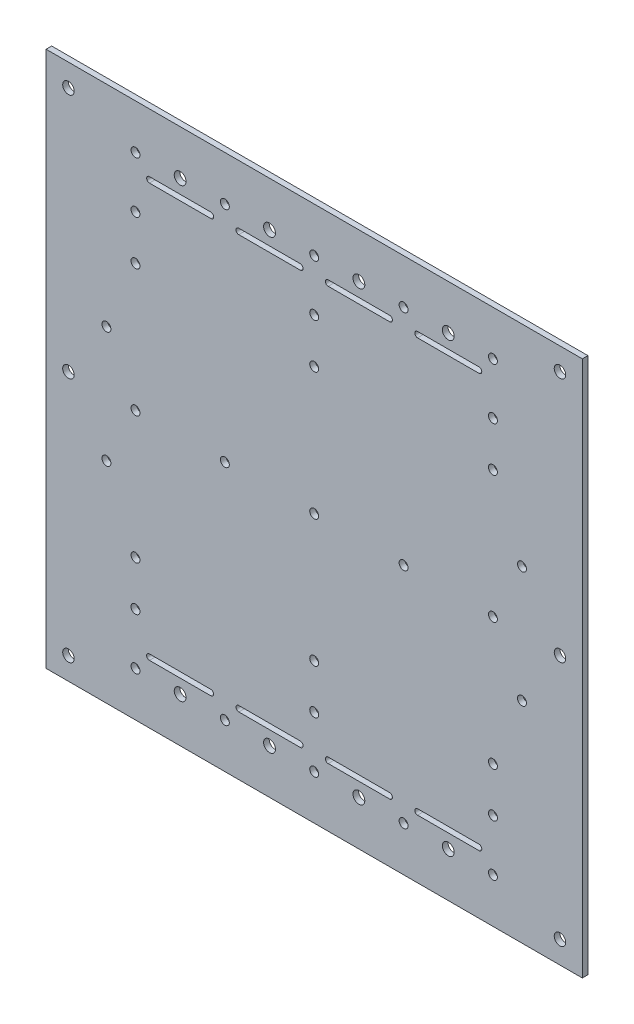
SolidWorks part; units mm, degrees
ref_plane "Front Plane" through (0, 0, 0) normal (0, 0, 1) x (1, 0, 0)
ref_plane "Top Plane" through (0, 0, 0) normal (0, 1, 0) x (1, 0, 0)
ref_plane "Right Plane" through (0, 0, 0) normal (1, 0, 0) x (0, 0, -1)
sketch "Sketch1" plane through (0, 0, 0) normal (0, 0, 1) x (1, 0, 0)
  line L0 (-152.4, 127) -> (-76.2, 127) construction
  line L1 (-152.4, 152.4) -> (152.4, 152.4)
  line L2 (-152.4, 152.4) -> (-152.4, -152.4)
  line L3 (-152.4, -152.4) -> (152.4, -152.4)
  line L4 (152.4, 152.4) -> (152.4, -152.4)
  line L5 (-76.2, 127) -> (-25.4, 127) construction
  line L6 (-25.4, 127) -> (25.4, 127) construction
  line L7 (25.4, 127) -> (76.2, 127) construction
  line L8 (76.2, 127) -> (152.4, 127) construction
  line L9 (-152.4, 0) -> (152.4, 0) construction
  line L10 (0, 152.4) -> (0, -152.4) construction
  line L11 (-118.11, 152.4) -> (-118.11, -152.4) construction
  line L12 (-152.4, -127) -> (152.4, -127) construction
  line L13 (127, 152.4) -> (127, -152.4) construction
  line L14 (-50.8, 152.4) -> (-50.8, -152.4) construction
  line L15 (50.8, 152.4) -> (50.8, -152.4) construction
  line L16 (-101.6, 152.4) -> (-101.6, -152.4) construction
  line L17 (-95.25, 66.04) -> (-57.15, 66.04) construction
  line L18 (-95.25, 66.04) -> (-95.25, -66.04) construction
  line L19 (-95.25, -66.04) -> (-57.15, -66.04) construction
  line L20 (-57.15, 66.04) -> (-57.15, -66.04) construction
  line L21 (-44.45, 66.04) -> (-6.35, 66.04) construction
  line L22 (-44.45, 66.04) -> (-44.45, -66.04) construction
  line L23 (-44.45, -66.04) -> (-6.35, -66.04) construction
  line L24 (-6.35, 66.04) -> (-6.35, -66.04) construction
  line L25 (6.35, 66.04) -> (44.45, 66.04) construction
  line L26 (6.35, 66.04) -> (6.35, -66.04) construction
  line L27 (6.35, -66.04) -> (44.45, -66.04) construction
  line L28 (44.45, 66.04) -> (44.45, -66.04) construction
  line L29 (57.15, 66.04) -> (95.25, 66.04) construction
  line L30 (57.15, 66.04) -> (57.15, -66.04) construction
  line L31 (57.15, -66.04) -> (95.25, -66.04) construction
  line L32 (95.25, 66.04) -> (95.25, -66.04) construction
  line L33 (101.6, 152.4) -> (101.6, -152.4) construction
  line L34 (-152.4, 120.65) -> (152.4, 120.65) construction
  line L35 (-101.6, 39.7057) -> (-95.25, 39.7057) construction
  line L36 (-57.15, 39.7057) -> (-50.8, 39.7057) construction
  line L37 (-76.2, 66.04) -> (-76.2, 0) construction
  line L38 (-76.2, 0) -> (-76.2, -66.04) construction
  line L39 (-152.4, 72.39) -> (152.4, 72.39) construction
  line L40 (-152.4, -72.39) -> (152.4, -72.39) construction
  line L41 (-76.2, 66.04) -> (-76.2, 72.39) construction
  line L42 (-95.25, -66.04) -> (-95.25, -72.39) construction
  line L43 (95.25, 39.7057) -> (101.6, 39.7057) construction
  line L44 (-95.25, 111.76) -> (-57.15, 111.76) construction
  line L45 (-57.15, 111.76) -> (-57.15, 118.4779) construction
  line L46 (-94.0266, 120.65) -> (-78.1749, 130.2582) construction
  line L47 (-95.25, 111.76) -> (-95.25, 118.4779) construction
  line L48 (-58.3734, 120.65) -> (-74.2251, 130.2582) construction
  line L49 (-107.3169, 130.81) -> (-83.1894, 130.81) construction
  line L50 (-6.35, 111.76) -> (-6.35, 118.4779) construction
  line L51 (-7.5734, 120.65) -> (-23.4251, 130.2582) construction
  line L52 (-43.2266, 120.65) -> (-27.3749, 130.2582) construction
  line L53 (-44.45, 111.76) -> (-44.45, 118.4779) construction
  line L54 (-6.35, 111.76) -> (-44.45, 111.76) construction
  line L55 (44.45, 111.76) -> (44.45, 118.4779) construction
  line L56 (43.2266, 120.65) -> (27.3749, 130.2582) construction
  line L57 (7.5734, 120.65) -> (23.4251, 130.2582) construction
  line L58 (6.35, 111.76) -> (6.35, 118.4779) construction
  line L59 (6.35, 111.76) -> (44.45, 111.76) construction
  line L60 (95.25, 111.76) -> (57.15, 111.76) construction
  line L61 (95.25, 111.76) -> (95.25, 118.4779) construction
  line L62 (94.0266, 120.65) -> (78.1749, 130.2582) construction
  line L63 (58.3734, 120.65) -> (74.2251, 130.2582) construction
  line L64 (57.15, 111.76) -> (57.15, 118.4779) construction
  line L65 (-95.25, -111.76) -> (-95.25, -118.4779) construction
  line L66 (-94.0266, -120.65) -> (-78.1749, -130.2582) construction
  line L67 (-58.3734, -120.65) -> (-74.2251, -130.2582) construction
  line L68 (-95.25, -111.76) -> (-57.15, -111.76) construction
  line L69 (-57.15, -111.76) -> (-57.15, -118.4779) construction
  line L70 (-44.45, -111.76) -> (-44.45, -118.4779) construction
  line L71 (-43.2266, -120.65) -> (-27.3749, -130.2582) construction
  line L72 (-6.35, -111.76) -> (-44.45, -111.76) construction
  line L73 (-7.5734, -120.65) -> (-23.4251, -130.2582) construction
  line L74 (-6.35, -111.76) -> (-6.35, -118.4779) construction
  line L75 (6.35, -111.76) -> (6.35, -118.4779) construction
  line L76 (7.5734, -120.65) -> (23.4251, -130.2582) construction
  line L77 (43.2266, -120.65) -> (27.3749, -130.2582) construction
  line L78 (6.35, -111.76) -> (44.45, -111.76) construction
  line L79 (44.45, -111.76) -> (44.45, -118.4779) construction
  line L80 (57.15, -111.76) -> (57.15, -118.4779) construction
  line L81 (58.3734, -120.65) -> (74.2251, -130.2582) construction
  line L82 (94.0266, -120.65) -> (78.1749, -130.2582) construction
  line L83 (95.25, -111.76) -> (57.15, -111.76) construction
  line L84 (95.25, -111.76) -> (95.25, -118.4779) construction
  line L85 (-152.4, 97.79) -> (152.4, 97.79) construction
  line L86 (-50.8, 39.7057) -> (-44.45, 39.7057) construction
  line L87 (-127, 152.4) -> (-127, -152.4) construction
  line L89 (-95.25, 101.6) -> (-92.3192, 101.6) construction
  line L90 (-95.25, 101.6) -> (-95.25, -101.6) construction
  line L96 (-90.8538, 101.6) -> (-90.8538, 68.58) construction
  line L97 (-89.3885, 101.6) -> (-89.3885, 68.58) construction
  line L98 (-92.3192, 101.6) -> (-92.3192, 68.58) construction
  line L99 (-83.5269, 101.6) -> (-83.5269, 68.58) construction
  line L100 (-86.4577, 101.6) -> (-86.4577, 68.58) construction
  line L101 (-89.3885, 101.6) -> (-86.4577, 101.6) construction
  line L102 (-77.6654, 101.6) -> (-77.6654, 68.58) construction
  line L103 (-80.5962, 101.6) -> (-80.5962, 68.58) construction
  line L104 (-83.5269, 101.6) -> (-80.5962, 101.6) construction
  line L105 (-71.8038, 101.6) -> (-71.8038, 68.58) construction
  line L106 (-74.7346, 101.6) -> (-74.7346, 68.58) construction
  line L107 (-77.6654, 101.6) -> (-74.7346, 101.6) construction
  line L108 (-65.9423, 101.6) -> (-65.9423, 68.58) construction
  line L109 (-68.8731, 101.6) -> (-68.8731, 68.58) construction
  line L110 (-71.8038, 101.6) -> (-68.8731, 101.6) construction
  line L111 (-60.0808, 101.6) -> (-60.0808, 68.58) construction
  line L112 (-63.0115, 101.6) -> (-63.0115, 68.58) construction
  line L113 (-65.9423, 101.6) -> (-63.0115, 101.6) construction
  line L114 (-57.15, -101.6) -> (-57.15, 101.6) construction
  line L115 (-60.0808, 101.6) -> (-57.15, 101.6) construction
  line L116 (-92.3192, 68.58) -> (-89.3885, 68.58) construction
  line L117 (-60.0808, -101.6) -> (-57.15, -101.6) construction
  line L118 (-60.0808, -101.6) -> (-60.0808, -68.58) construction
  line L119 (-63.0115, -101.6) -> (-63.0115, -68.58) construction
  line L120 (-65.9423, -101.6) -> (-65.9423, -68.58) construction
  line L121 (-65.9423, -101.6) -> (-63.0115, -101.6) construction
  line L122 (-68.8731, -101.6) -> (-68.8731, -68.58) construction
  line L123 (-71.8038, -101.6) -> (-68.8731, -101.6) construction
  line L124 (-71.8038, -101.6) -> (-71.8038, -68.58) construction
  line L125 (-74.7346, -101.6) -> (-74.7346, -68.58) construction
  line L126 (-77.6654, -101.6) -> (-74.7346, -101.6) construction
  line L127 (-77.6654, -101.6) -> (-77.6654, -68.58) construction
  line L128 (-80.5962, -101.6) -> (-80.5962, -68.58) construction
  line L129 (-83.5269, -101.6) -> (-80.5962, -101.6) construction
  line L130 (-83.5269, -101.6) -> (-83.5269, -68.58) construction
  line L131 (-86.4577, -101.6) -> (-86.4577, -68.58) construction
  line L132 (-89.3885, -101.6) -> (-86.4577, -101.6) construction
  line L133 (-89.3885, -101.6) -> (-89.3885, -68.58) construction
  line L134 (-92.3192, -101.6) -> (-92.3192, -68.58) construction
  line L135 (-95.25, -101.6) -> (-92.3192, -101.6) construction
  line L136 (-9.2808, 68.58) -> (-12.2115, 68.58) construction
  line L137 (6.35, 66.04) -> (44.45, 66.04) construction
  line L138 (-6.35, -66.04) -> (-6.35, -72.39) construction
  line L139 (-25.4, 66.04) -> (-25.4, 72.39) construction
  line L140 (-25.4, 0) -> (-25.4, -66.04) construction
  line L141 (-25.4, 66.04) -> (-25.4, 0) construction
  line L142 (-44.45, 66.04) -> (-44.45, -66.04) construction
  line L143 (-6.35, -66.04) -> (-44.45, -66.04) construction
  line L144 (-6.35, 66.04) -> (-6.35, -66.04) construction
  line L145 (-6.35, 66.04) -> (-44.45, 66.04) construction
  line L146 (-6.35, -101.6) -> (-9.2808, -101.6) construction
  line L147 (-9.2808, -101.6) -> (-9.2808, -68.58) construction
  line L148 (-12.2115, -101.6) -> (-12.2115, -68.58) construction
  line L149 (-12.2115, -101.6) -> (-15.1423, -101.6) construction
  line L150 (-15.1423, -101.6) -> (-15.1423, -68.58) construction
  line L151 (-18.0731, -101.6) -> (-18.0731, -68.58) construction
  line L152 (-18.0731, -101.6) -> (-21.0038, -101.6) construction
  line L153 (-21.0038, -101.6) -> (-21.0038, -68.58) construction
  line L154 (-23.9346, -101.6) -> (-23.9346, -68.58) construction
  line L155 (-23.9346, -101.6) -> (-26.8654, -101.6) construction
  line L156 (-26.8654, -101.6) -> (-26.8654, -68.58) construction
  line L157 (-29.7962, -101.6) -> (-29.7962, -68.58) construction
  line L158 (-29.7962, -101.6) -> (-32.7269, -101.6) construction
  line L159 (-32.7269, -101.6) -> (-32.7269, -68.58) construction
  line L160 (-35.6577, -101.6) -> (-38.5885, -101.6) construction
  line L161 (-35.6577, -101.6) -> (-35.6577, -68.58) construction
  line L162 (-38.5885, -101.6) -> (-38.5885, -68.58) construction
  line L163 (-41.5192, -101.6) -> (-41.5192, -68.58) construction
  line L164 (-41.5192, -101.6) -> (-44.45, -101.6) construction
  line L165 (-41.5192, 101.6) -> (-44.45, 101.6) construction
  line L166 (-44.45, -101.6) -> (-44.45, 101.6) construction
  line L167 (-35.6577, 101.6) -> (-38.5885, 101.6) construction
  line L168 (-38.5885, 101.6) -> (-38.5885, 68.58) construction
  line L169 (-41.5192, 101.6) -> (-41.5192, 68.58) construction
  line L170 (-29.7962, 101.6) -> (-32.7269, 101.6) construction
  line L171 (-32.7269, 101.6) -> (-32.7269, 68.58) construction
  line L172 (-35.6577, 101.6) -> (-35.6577, 68.58) construction
  line L173 (-23.9346, 101.6) -> (-26.8654, 101.6) construction
  line L174 (-26.8654, 101.6) -> (-26.8654, 68.58) construction
  line L175 (-29.7962, 101.6) -> (-29.7962, 68.58) construction
  line L176 (-18.0731, 101.6) -> (-21.0038, 101.6) construction
  line L177 (-21.0038, 101.6) -> (-21.0038, 68.58) construction
  line L178 (-23.9346, 101.6) -> (-23.9346, 68.58) construction
  line L179 (-12.2115, 101.6) -> (-15.1423, 101.6) construction
  line L180 (-15.1423, 101.6) -> (-15.1423, 68.58) construction
  line L181 (-18.0731, 101.6) -> (-18.0731, 68.58) construction
  line L182 (-9.2808, 101.6) -> (-9.2808, 68.58) construction
  line L183 (-12.2115, 101.6) -> (-12.2115, 68.58) construction
  line L184 (-6.35, 101.6) -> (-6.35, -101.6) construction
  line L185 (-6.35, 101.6) -> (-9.2808, 101.6) construction
  line L186 (6.35, 66.04) -> (6.35, -66.04) construction
  line L187 (6.35, -66.04) -> (44.45, -66.04) construction
  line L188 (44.45, 66.04) -> (44.45, -66.04) construction
  line L189 (25.4, 66.04) -> (25.4, 0) construction
  line L190 (25.4, 0) -> (25.4, -66.04) construction
  line L191 (25.4, 66.04) -> (25.4, 72.39) construction
  line L192 (6.35, -66.04) -> (6.35, -72.39) construction
  line L193 (9.2808, 68.58) -> (12.2115, 68.58) construction
  line L194 (6.35, 66.04) -> (6.35, -66.04) construction
  line L195 (44.45, -66.04) -> (6.35, -66.04) construction
  line L196 (44.45, 66.04) -> (44.45, -66.04) construction
  line L197 (44.45, 66.04) -> (6.35, 66.04) construction
  line L198 (6.35, 101.6) -> (9.2808, 101.6) construction
  line L199 (6.35, 101.6) -> (6.35, -101.6) construction
  line L200 (12.2115, 101.6) -> (12.2115, 68.58) construction
  line L201 (9.2808, 101.6) -> (9.2808, 68.58) construction
  line L202 (18.0731, 101.6) -> (18.0731, 68.58) construction
  line L203 (15.1423, 101.6) -> (15.1423, 68.58) construction
  line L204 (12.2115, 101.6) -> (15.1423, 101.6) construction
  line L205 (23.9346, 101.6) -> (23.9346, 68.58) construction
  line L206 (21.0038, 101.6) -> (21.0038, 68.58) construction
  line L207 (18.0731, 101.6) -> (21.0038, 101.6) construction
  line L208 (29.7962, 101.6) -> (29.7962, 68.58) construction
  line L209 (26.8654, 101.6) -> (26.8654, 68.58) construction
  line L210 (23.9346, 101.6) -> (26.8654, 101.6) construction
  line L211 (35.6577, 101.6) -> (35.6577, 68.58) construction
  line L212 (32.7269, 101.6) -> (32.7269, 68.58) construction
  line L213 (29.7962, 101.6) -> (32.7269, 101.6) construction
  line L214 (41.5192, 101.6) -> (41.5192, 68.58) construction
  line L215 (38.5885, 101.6) -> (38.5885, 68.58) construction
  line L216 (35.6577, 101.6) -> (38.5885, 101.6) construction
  line L217 (44.45, -101.6) -> (44.45, 101.6) construction
  line L218 (41.5192, 101.6) -> (44.45, 101.6) construction
  line L219 (41.5192, -101.6) -> (44.45, -101.6) construction
  line L220 (41.5192, -101.6) -> (41.5192, -68.58) construction
  line L221 (38.5885, -101.6) -> (38.5885, -68.58) construction
  line L222 (35.6577, -101.6) -> (35.6577, -68.58) construction
  line L223 (35.6577, -101.6) -> (38.5885, -101.6) construction
  line L224 (32.7269, -101.6) -> (32.7269, -68.58) construction
  line L225 (29.7962, -101.6) -> (32.7269, -101.6) construction
  line L226 (29.7962, -101.6) -> (29.7962, -68.58) construction
  line L227 (26.8654, -101.6) -> (26.8654, -68.58) construction
  line L228 (23.9346, -101.6) -> (26.8654, -101.6) construction
  line L229 (23.9346, -101.6) -> (23.9346, -68.58) construction
  line L230 (21.0038, -101.6) -> (21.0038, -68.58) construction
  line L231 (18.0731, -101.6) -> (21.0038, -101.6) construction
  line L232 (18.0731, -101.6) -> (18.0731, -68.58) construction
  line L233 (15.1423, -101.6) -> (15.1423, -68.58) construction
  line L234 (12.2115, -101.6) -> (15.1423, -101.6) construction
  line L235 (12.2115, -101.6) -> (12.2115, -68.58) construction
  line L236 (9.2808, -101.6) -> (9.2808, -68.58) construction
  line L237 (6.35, -101.6) -> (9.2808, -101.6) construction
  line L238 (57.15, 66.04) -> (95.25, 66.04) construction
  line L239 (57.15, 66.04) -> (57.15, -66.04) construction
  line L240 (57.15, -66.04) -> (95.25, -66.04) construction
  line L241 (95.25, 66.04) -> (95.25, -66.04) construction
  line L242 (92.3192, 68.58) -> (89.3885, 68.58) construction
  line L243 (95.25, -66.04) -> (95.25, -72.39) construction
  line L244 (76.2, 66.04) -> (76.2, 72.39) construction
  line L245 (76.2, 0) -> (76.2, -66.04) construction
  line L246 (76.2, 66.04) -> (76.2, 0) construction
  line L247 (57.15, 66.04) -> (57.15, -66.04) construction
  line L248 (95.25, -66.04) -> (57.15, -66.04) construction
  line L249 (95.25, 66.04) -> (95.25, -66.04) construction
  line L250 (95.25, 66.04) -> (57.15, 66.04) construction
  line L251 (57.15, 66.04) -> (57.15, -66.04) construction
  line L252 (95.25, -66.04) -> (57.15, -66.04) construction
  line L253 (95.25, 66.04) -> (95.25, -66.04) construction
  line L254 (95.25, 66.04) -> (57.15, 66.04) construction
  line L255 (95.25, -101.6) -> (92.3192, -101.6) construction
  line L256 (92.3192, -101.6) -> (92.3192, -68.58) construction
  line L257 (89.3885, -101.6) -> (89.3885, -68.58) construction
  line L258 (89.3885, -101.6) -> (86.4577, -101.6) construction
  line L259 (86.4577, -101.6) -> (86.4577, -68.58) construction
  line L260 (83.5269, -101.6) -> (83.5269, -68.58) construction
  line L261 (83.5269, -101.6) -> (80.5962, -101.6) construction
  line L262 (80.5962, -101.6) -> (80.5962, -68.58) construction
  line L263 (77.6654, -101.6) -> (77.6654, -68.58) construction
  line L264 (77.6654, -101.6) -> (74.7346, -101.6) construction
  line L265 (74.7346, -101.6) -> (74.7346, -68.58) construction
  line L266 (71.8038, -101.6) -> (71.8038, -68.58) construction
  line L267 (71.8038, -101.6) -> (68.8731, -101.6) construction
  line L268 (68.8731, -101.6) -> (68.8731, -68.58) construction
  line L269 (65.9423, -101.6) -> (63.0115, -101.6) construction
  line L270 (65.9423, -101.6) -> (65.9423, -68.58) construction
  line L271 (63.0115, -101.6) -> (63.0115, -68.58) construction
  line L272 (60.0808, -101.6) -> (60.0808, -68.58) construction
  line L273 (60.0808, -101.6) -> (57.15, -101.6) construction
  line L274 (60.0808, 101.6) -> (57.15, 101.6) construction
  line L275 (57.15, -101.6) -> (57.15, 101.6) construction
  line L276 (65.9423, 101.6) -> (63.0115, 101.6) construction
  line L277 (63.0115, 101.6) -> (63.0115, 68.58) construction
  line L278 (60.0808, 101.6) -> (60.0808, 68.58) construction
  line L279 (71.8038, 101.6) -> (68.8731, 101.6) construction
  line L280 (68.8731, 101.6) -> (68.8731, 68.58) construction
  line L281 (65.9423, 101.6) -> (65.9423, 68.58) construction
  line L282 (77.6654, 101.6) -> (74.7346, 101.6) construction
  line L283 (74.7346, 101.6) -> (74.7346, 68.58) construction
  line L284 (71.8038, 101.6) -> (71.8038, 68.58) construction
  line L285 (83.5269, 101.6) -> (80.5962, 101.6) construction
  line L286 (80.5962, 101.6) -> (80.5962, 68.58) construction
  line L287 (77.6654, 101.6) -> (77.6654, 68.58) construction
  line L288 (89.3885, 101.6) -> (86.4577, 101.6) construction
  line L289 (86.4577, 101.6) -> (86.4577, 68.58) construction
  line L290 (83.5269, 101.6) -> (83.5269, 68.58) construction
  line L291 (92.3192, 101.6) -> (92.3192, 68.58) construction
  line L292 (89.3885, 101.6) -> (89.3885, 68.58) construction
  line L293 (95.25, 101.6) -> (95.25, -101.6) construction
  line L294 (95.25, 101.6) -> (92.3192, 101.6) construction
  line L295 (-101.6, 39.7057) -> (-107.95, 39.7057) construction
  line L296 (-101.6, 78.74) -> (101.6, 78.74) construction
  line L297 (-107.95, 72.39) -> (-107.95, -72.39) construction
  line L298 (-101.6, -78.74) -> (101.6, -78.74) construction
  line L299 (107.95, 72.39) -> (107.95, -72.39) construction
  line L300 (-97.0611, 78.74) -> (-97.0611, 72.39) construction
  line L301 (-107.95, 22.225) -> (-120.65, 22.225) construction
  line L302 (-127, 15.875) -> (-127, -15.875) construction
  line L303 (-120.65, -22.225) -> (-107.95, -22.225) construction
  line L304 (-93.6625, 117.475) -> (-58.7375, 117.475) construction
  line L305 (-93.6625, 119.0625) -> (-58.7375, 119.0625)
  line L306 (-93.6625, 115.8875) -> (-58.7375, 115.8875)
  line L307 (-7.9375, 117.475) -> (-42.8625, 117.475) construction
  line L308 (-7.9375, 119.0625) -> (-42.8625, 119.0625)
  line L309 (-7.9375, 115.8875) -> (-42.8625, 115.8875)
  line L310 (7.9375, 117.475) -> (42.8625, 117.475) construction
  line L311 (7.9375, 119.0625) -> (42.8625, 119.0625)
  line L312 (7.9375, 115.8875) -> (42.8625, 115.8875)
  line L313 (93.6625, 117.475) -> (58.7375, 117.475) construction
  line L314 (93.6625, 119.0625) -> (58.7375, 119.0625)
  line L315 (93.6625, 115.8875) -> (58.7375, 115.8875)
  line L316 (93.6625, -117.475) -> (58.7375, -117.475) construction
  line L317 (93.6625, -119.0625) -> (58.7375, -119.0625)
  line L318 (93.6625, -115.8875) -> (58.7375, -115.8875)
  line L319 (7.9375, -117.475) -> (42.8625, -117.475) construction
  line L320 (7.9375, -119.0625) -> (42.8625, -119.0625)
  line L321 (7.9375, -115.8875) -> (42.8625, -115.8875)
  line L322 (-7.9375, -117.475) -> (-42.8625, -117.475) construction
  line L323 (-7.9375, -119.0625) -> (-42.8625, -119.0625)
  line L324 (-7.9375, -115.8875) -> (-42.8625, -115.8875)
  line L325 (-93.6625, -117.475) -> (-58.7375, -117.475) construction
  line L326 (-93.6625, -119.0625) -> (-58.7375, -119.0625)
  line L327 (-93.6625, -115.8875) -> (-58.7375, -115.8875)
  line L328 (-6.35, 107.95) -> (-6.35, 95.25)
  line L329 (-95.25, 107.95) -> (-57.15, 107.95) construction
  line L330 (-95.25, 107.95) -> (-95.25, 95.25) construction
  line L331 (-95.25, 95.25) -> (-57.15, 95.25) construction
  line L332 (-57.15, 107.95) -> (-57.15, 95.25) construction
  line L333 (-6.35, 107.95) -> (-44.45, 107.95) construction
  line L334 (-44.45, 107.95) -> (-44.45, 95.25) construction
  line L335 (-6.35, 95.25) -> (-44.45, 95.25) construction
  line L336 (95.25, 95.25) -> (57.15, 95.25) construction
  line L337 (95.25, 107.95) -> (95.25, 95.25) construction
  line L338 (95.25, 107.95) -> (57.15, 107.95) construction
  line L339 (57.15, 107.95) -> (57.15, 95.25) construction
  line L340 (44.45, 107.95) -> (44.45, 95.25)
  line L341 (6.35, 95.25) -> (44.45, 95.25) construction
  line L342 (6.35, 107.95) -> (44.45, 107.95) construction
  line L343 (6.35, 107.95) -> (6.35, 95.25) construction
  line L344 (-95.25, -95.25) -> (-57.15, -95.25) construction
  line L345 (-95.25, -107.95) -> (-95.25, -95.25) construction
  line L346 (-95.25, -107.95) -> (-57.15, -107.95) construction
  line L347 (-57.15, -107.95) -> (-57.15, -95.25) construction
  line L348 (-44.45, -107.95) -> (-44.45, -95.25) construction
  line L349 (-6.35, -95.25) -> (-44.45, -95.25) construction
  line L350 (-6.35, -107.95) -> (-44.45, -107.95) construction
  line L351 (-6.35, -107.95) -> (-6.35, -95.25) construction
  line L352 (6.35, -107.95) -> (6.35, -95.25) construction
  line L353 (6.35, -95.25) -> (44.45, -95.25) construction
  line L354 (6.35, -107.95) -> (44.45, -107.95) construction
  line L355 (44.45, -107.95) -> (44.45, -95.25)
  line L356 (57.15, -107.95) -> (57.15, -95.25) construction
  line L357 (95.25, -107.95) -> (57.15, -107.95) construction
  line L358 (95.25, -107.95) -> (95.25, -95.25) construction
  line L359 (95.25, -95.25) -> (57.15, -95.25) construction
  circle A0 centre (-76.2, 127) radius 3.3655
  circle A1 centre (-25.4, 127) radius 3.3655
  circle A2 centre (25.4, 127) radius 3.3655
  circle A3 centre (76.2, 127) radius 3.3655
  circle A4 centre (-101.6, 0) radius 2.54
  circle A5 centre (-50.8, 0) radius 2.54
  circle A6 centre (0, 0) radius 2.54
  circle A7 centre (101.6, 0) radius 2.54
  circle A8 centre (50.8, 0) radius 2.54
  circle A9 centre (-50.8, 127) radius 2.54
  circle A10 centre (0, 127) radius 2.54
  circle A11 centre (50.8, 127) radius 2.54
  circle A12 centre (-101.6, 72.39) radius 2.54
  circle A13 centre (0, 72.39) radius 2.54
  circle A14 centre (101.6, 72.39) radius 2.54
  circle A15 centre (-101.6, -72.39) radius 2.54
  circle A16 centre (0, -72.39) radius 2.54
  circle A17 centre (101.6, -72.39) radius 2.54
  arc A18 (-74.2251, 130.2582) -> (-78.1749, 130.2582) centre (-76.2, 127) ccw construction
  arc A19 (-57.15, 118.4779) -> (-58.3734, 120.65) centre (-59.69, 118.4779) ccw construction
  arc A20 (-95.25, 118.4779) -> (-94.0266, 120.65) centre (-92.71, 118.4779) cw construction
  arc A21 (-6.35, 118.4779) -> (-7.5734, 120.65) centre (-8.89, 118.4779) ccw construction
  arc A22 (-27.3749, 130.2582) -> (-23.4251, 130.2582) centre (-25.4, 127) cw construction
  arc A23 (-44.45, 118.4779) -> (-43.2266, 120.65) centre (-41.91, 118.4779) cw construction
  arc A24 (44.45, 118.4779) -> (43.2266, 120.65) centre (41.91, 118.4779) ccw construction
  arc A25 (27.3749, 130.2582) -> (23.4251, 130.2582) centre (25.4, 127) ccw construction
  arc A26 (6.35, 118.4779) -> (7.5734, 120.65) centre (8.89, 118.4779) cw construction
  arc A27 (95.25, 118.4779) -> (94.0266, 120.65) centre (92.71, 118.4779) ccw construction
  arc A28 (74.2251, 130.2582) -> (78.1749, 130.2582) centre (76.2, 127) cw construction
  arc A29 (57.15, 118.4779) -> (58.3734, 120.65) centre (59.69, 118.4779) cw construction
  circle A30 centre (-76.2, -127) radius 3.3655
  circle A31 centre (-25.4, -127) radius 3.3655
  circle A32 centre (25.4, -127) radius 3.3655
  circle A33 centre (76.2, -127) radius 3.3655
  arc A34 (-95.25, -118.4779) -> (-94.0266, -120.65) centre (-92.71, -118.4779) ccw construction
  arc A35 (-74.2251, -130.2582) -> (-78.1749, -130.2582) centre (-76.2, -127) cw construction
  arc A36 (-57.15, -118.4779) -> (-58.3734, -120.65) centre (-59.69, -118.4779) cw construction
  arc A37 (-44.45, -118.4779) -> (-43.2266, -120.65) centre (-41.91, -118.4779) ccw construction
  arc A38 (-27.3749, -130.2582) -> (-23.4251, -130.2582) centre (-25.4, -127) ccw construction
  arc A39 (-6.35, -118.4779) -> (-7.5734, -120.65) centre (-8.89, -118.4779) cw construction
  arc A40 (6.35, -118.4779) -> (7.5734, -120.65) centre (8.89, -118.4779) ccw construction
  arc A41 (27.3749, -130.2582) -> (23.4251, -130.2582) centre (25.4, -127) cw construction
  arc A42 (44.45, -118.4779) -> (43.2266, -120.65) centre (41.91, -118.4779) cw construction
  arc A43 (57.15, -118.4779) -> (58.3734, -120.65) centre (59.69, -118.4779) ccw construction
  arc A44 (74.2251, -130.2582) -> (78.1749, -130.2582) centre (76.2, -127) ccw construction
  arc A45 (95.25, -118.4779) -> (94.0266, -120.65) centre (92.71, -118.4779) cw construction
  circle A46 centre (50.8, -127) radius 2.54
  circle A47 centre (0, -127) radius 2.54
  circle A48 centre (-50.8, -127) radius 2.54
  circle A49 centre (-101.6, 97.79) radius 2.54
  circle A50 centre (0, 97.79) radius 2.54
  circle A51 centre (101.6, 97.79) radius 2.54
  circle A52 centre (101.6, 127) radius 2.54
  circle A53 centre (-101.6, 127) radius 2.54
  circle A54 centre (-118.11, 33.02) radius 2.54
  circle A56 centre (-101.6, -127) radius 2.54
  circle A57 centre (101.6, -127) radius 2.54
  circle A58 centre (101.6, -97.79) radius 2.54
  circle A59 centre (0, -97.79) radius 2.54
  circle A60 centre (-101.6, -97.79) radius 2.54
  circle A61 centre (-118.11, -33.02) radius 2.54
  circle A63 centre (-139.7, 139.7) radius 3.2639
  circle A64 centre (-139.7, 0) radius 3.2639
  circle A65 centre (-139.7, -139.7) radius 3.2639
  circle A66 centre (139.7, -139.7) radius 3.2639
  circle A67 centre (139.7, 0) radius 3.2639
  circle A68 centre (139.7, 139.7) radius 3.2639
  arc A70 (-92.3192, 68.58) -> (-89.3885, 68.58) centre (-90.8538, 68.58) ccw construction
  arc A71 (-86.4577, 68.58) -> (-83.5269, 68.58) centre (-84.9923, 68.58) ccw construction
  arc A72 (-80.5962, 68.58) -> (-77.6654, 68.58) centre (-79.1308, 68.58) ccw construction
  arc A73 (-74.7346, 68.58) -> (-71.8038, 68.58) centre (-73.2692, 68.58) ccw construction
  arc A74 (-68.8731, 68.58) -> (-65.9423, 68.58) centre (-67.4077, 68.58) ccw construction
  arc A75 (-63.0115, 68.58) -> (-60.0808, 68.58) centre (-61.5462, 68.58) ccw construction
  arc A76 (-63.0115, -68.58) -> (-60.0808, -68.58) centre (-61.5462, -68.58) cw construction
  arc A77 (-68.8731, -68.58) -> (-65.9423, -68.58) centre (-67.4077, -68.58) cw construction
  arc A78 (-74.7346, -68.58) -> (-71.8038, -68.58) centre (-73.2692, -68.58) cw construction
  arc A79 (-80.5962, -68.58) -> (-77.6654, -68.58) centre (-79.1308, -68.58) cw construction
  arc A80 (-86.4577, -68.58) -> (-83.5269, -68.58) centre (-84.9923, -68.58) cw construction
  arc A81 (-92.3192, -68.58) -> (-89.3885, -68.58) centre (-90.8538, -68.58) cw construction
  arc A82 (-9.2808, -68.58) -> (-12.2115, -68.58) centre (-10.7462, -68.58) ccw construction
  arc A83 (-15.1423, -68.58) -> (-18.0731, -68.58) centre (-16.6077, -68.58) ccw construction
  arc A84 (-21.0038, -68.58) -> (-23.9346, -68.58) centre (-22.4692, -68.58) ccw construction
  arc A85 (-26.8654, -68.58) -> (-29.7962, -68.58) centre (-28.3308, -68.58) ccw construction
  arc A86 (-32.7269, -68.58) -> (-35.6577, -68.58) centre (-34.1923, -68.58) ccw construction
  arc A87 (-38.5885, -68.58) -> (-41.5192, -68.58) centre (-40.0538, -68.58) ccw construction
  arc A88 (-38.5885, 68.58) -> (-41.5192, 68.58) centre (-40.0538, 68.58) cw construction
  arc A89 (-32.7269, 68.58) -> (-35.6577, 68.58) centre (-34.1923, 68.58) cw construction
  arc A90 (-26.8654, 68.58) -> (-29.7962, 68.58) centre (-28.3308, 68.58) cw construction
  arc A91 (-21.0038, 68.58) -> (-23.9346, 68.58) centre (-22.4692, 68.58) cw construction
  arc A92 (-15.1423, 68.58) -> (-18.0731, 68.58) centre (-16.6077, 68.58) cw construction
  arc A93 (-9.2808, 68.58) -> (-12.2115, 68.58) centre (-10.7462, 68.58) cw construction
  arc A94 (9.2808, 68.58) -> (12.2115, 68.58) centre (10.7462, 68.58) ccw construction
  arc A95 (15.1423, 68.58) -> (18.0731, 68.58) centre (16.6077, 68.58) ccw construction
  arc A96 (21.0038, 68.58) -> (23.9346, 68.58) centre (22.4692, 68.58) ccw construction
  arc A97 (26.8654, 68.58) -> (29.7962, 68.58) centre (28.3308, 68.58) ccw construction
  arc A98 (32.7269, 68.58) -> (35.6577, 68.58) centre (34.1923, 68.58) ccw construction
  arc A99 (38.5885, 68.58) -> (41.5192, 68.58) centre (40.0538, 68.58) ccw construction
  arc A100 (38.5885, -68.58) -> (41.5192, -68.58) centre (40.0538, -68.58) cw construction
  arc A101 (32.7269, -68.58) -> (35.6577, -68.58) centre (34.1923, -68.58) cw construction
  arc A102 (26.8654, -68.58) -> (29.7962, -68.58) centre (28.3308, -68.58) cw construction
  arc A103 (21.0038, -68.58) -> (23.9346, -68.58) centre (22.4692, -68.58) cw construction
  arc A104 (15.1423, -68.58) -> (18.0731, -68.58) centre (16.6077, -68.58) cw construction
  arc A105 (9.2808, -68.58) -> (12.2115, -68.58) centre (10.7462, -68.58) cw construction
  arc A106 (92.3192, -68.58) -> (89.3885, -68.58) centre (90.8538, -68.58) ccw construction
  arc A107 (86.4577, -68.58) -> (83.5269, -68.58) centre (84.9923, -68.58) ccw construction
  arc A108 (80.5962, -68.58) -> (77.6654, -68.58) centre (79.1308, -68.58) ccw construction
  arc A109 (74.7346, -68.58) -> (71.8038, -68.58) centre (73.2692, -68.58) ccw construction
  arc A110 (68.8731, -68.58) -> (65.9423, -68.58) centre (67.4077, -68.58) ccw construction
  arc A111 (63.0115, -68.58) -> (60.0808, -68.58) centre (61.5462, -68.58) ccw construction
  arc A112 (63.0115, 68.58) -> (60.0808, 68.58) centre (61.5462, 68.58) cw construction
  arc A113 (68.8731, 68.58) -> (65.9423, 68.58) centre (67.4077, 68.58) cw construction
  arc A114 (74.7346, 68.58) -> (71.8038, 68.58) centre (73.2692, 68.58) cw construction
  arc A115 (80.5962, 68.58) -> (77.6654, 68.58) centre (79.1308, 68.58) cw construction
  arc A116 (86.4577, 68.58) -> (83.5269, 68.58) centre (84.9923, 68.58) cw construction
  arc A117 (92.3192, 68.58) -> (89.3885, 68.58) centre (90.8538, 68.58) cw construction
  arc A118 (-101.6, 78.74) -> (-107.95, 72.39) centre (-101.6, 72.39) ccw construction
  arc A119 (-107.95, -72.39) -> (-101.6, -78.74) centre (-101.6, -72.39) ccw construction
  arc A120 (101.6, 78.74) -> (107.95, 72.39) centre (101.6, 72.39) cw construction
  arc A121 (101.6, -78.74) -> (107.95, -72.39) centre (101.6, -72.39) ccw construction
  arc A122 (-127, -15.875) -> (-120.65, -22.225) centre (-120.65, -15.875) ccw construction
  arc A123 (-120.65, 22.225) -> (-127, 15.875) centre (-120.65, 15.875) ccw construction
  arc A124 (-93.6625, 119.0625) -> (-93.6625, 115.8875) centre (-93.6625, 117.475) ccw
  arc A125 (-58.7375, 115.8875) -> (-58.7375, 119.0625) centre (-58.7375, 117.475) ccw
  arc A126 (-7.9375, 119.0625) -> (-7.9375, 115.8875) centre (-7.9375, 117.475) cw
  arc A127 (-42.8625, 115.8875) -> (-42.8625, 119.0625) centre (-42.8625, 117.475) cw
  arc A128 (7.9375, 119.0625) -> (7.9375, 115.8875) centre (7.9375, 117.475) ccw
  arc A129 (42.8625, 115.8875) -> (42.8625, 119.0625) centre (42.8625, 117.475) ccw
  arc A130 (93.6625, 119.0625) -> (93.6625, 115.8875) centre (93.6625, 117.475) cw
  arc A131 (58.7375, 115.8875) -> (58.7375, 119.0625) centre (58.7375, 117.475) cw
  arc A132 (93.6625, -119.0625) -> (93.6625, -115.8875) centre (93.6625, -117.475) ccw
  arc A133 (58.7375, -115.8875) -> (58.7375, -119.0625) centre (58.7375, -117.475) ccw
  arc A134 (7.9375, -119.0625) -> (7.9375, -115.8875) centre (7.9375, -117.475) cw
  arc A135 (42.8625, -115.8875) -> (42.8625, -119.0625) centre (42.8625, -117.475) cw
  arc A136 (-7.9375, -119.0625) -> (-7.9375, -115.8875) centre (-7.9375, -117.475) ccw
  arc A137 (-42.8625, -115.8875) -> (-42.8625, -119.0625) centre (-42.8625, -117.475) ccw
  arc A138 (-93.6625, -119.0625) -> (-93.6625, -115.8875) centre (-93.6625, -117.475) cw
  arc A139 (-58.7375, -115.8875) -> (-58.7375, -119.0625) centre (-58.7375, -117.475) cw
  circle A140 centre (118.11, 33.02) radius 2.54
  circle A141 centre (118.11, -33.02) radius 2.54
  point P10 (-76.2, 111.76)
  point P63 (50.8, 127)
  point P95 (-76.2, 66.04)
  point P97 (-25.4, 66.04)
  point P99 (25.4, 66.04)
  point P101 (76.2, 66.04)
  point P116 (-95.25, 0)
  point P118 (-44.45, 0)
  point P119 (6.35, 0)
  point P120 (57.15, 0)
  point P219 (-76.2, 33.02)
  point P259 (0, 78.74)
  point P260 (-107.95, 0)
  point P545 (-127, 0)
  point P548 (-127, -22.225)
  point P551 (-127, 22.225)
  point P554 (-76.2, 117.475)
  point P562 (-25.4, 117.475)
  point P569 (25.4, 117.475)
  point P576 (76.2, 117.475)
  point P583 (76.2, -117.475)
  point P590 (25.4, -117.475)
  point P597 (-25.4, -117.475)
  point P604 (-76.2, -117.475)
  point P612 (-57.15, 101.6)
  point P613 (-58.6154, 101.6)
  dimension "D1" = 6.731
  dimension "D7" = 5.08
  dimension "D11" = 7.62
  dimension "D13" = 2.54
  dimension "D19" = 6.5278
  dimension "D25" = 6.35
  dimension "D26" = 6.35
  dimension "D27" = 6.35
  dimension "D29" = 6.35
  dimension "D2" = 25.4
  dimension "D3" = 50.8
  dimension "D4" = 25.4
  dimension "D5" = 25.4
  dimension "D6" = 25.4
  dimension "D8" = 38.1
  dimension "D9" = 31.75
  dimension "D10" = 132.08
  dimension "D12" = 19.05
  dimension "D14" = 25.4
  dimension "D15" = 304.8
  dimension "D16" = 304.8
  dimension "D17" = 8.89
  dimension "D18" = 12.7
  dimension "D20" = 12.7
  dimension "D21" = 12.7
  dimension "D23" = 33.02
  dimension "D24" = 10.16
  dimension "D28" = 44.45
  dimension "D30" = 3.175
  dimension "D31" = 12.7
  dimension "D32" = 3.175
  dimension "D22" = 6
extrude "Boss-Extrude1" add sketch "Sketch1" along normal blind 3.175 contours L4 L1 L2 L3 A67 A141 A60 A58 A56 A140 A54 A53 A52 A51 A50 A49 A47 L84 A45 L82 A44 L81 A43 L80 L83 L74 A39 L73 A38 L71 A37 L70 L72 L64 A29
